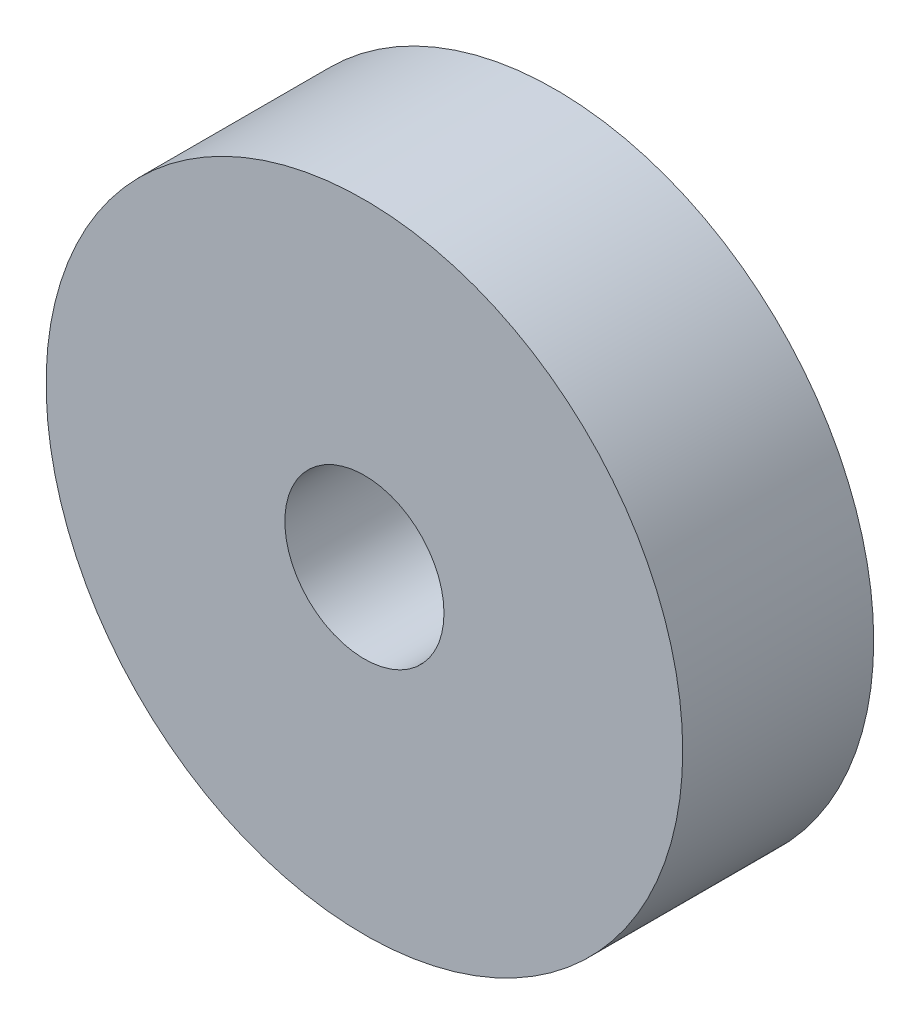
SolidWorks part; units mm, degrees
ref_plane "Front Plane" through (0, 0, 0) normal (0, 0, 1) x (1, 0, 0)
ref_plane "Top Plane" through (0, 0, 0) normal (0, 1, 0) x (1, 0, 0)
ref_plane "Right Plane" through (0, 0, 0) normal (1, 0, 0) x (0, 0, -1)
sketch "Sketch1" plane through (0, 0, 0) normal (0, 0, 1) x (1, 0, 0)
  circle A0 centre (0, 0) radius 2.5
  circle A1 centre (0, 0) radius 10
  dimension "D1" = 20
  dimension "D2" = 5
extrude "Boss-Extrude1" add sketch "Sketch1" along normal blind 6
